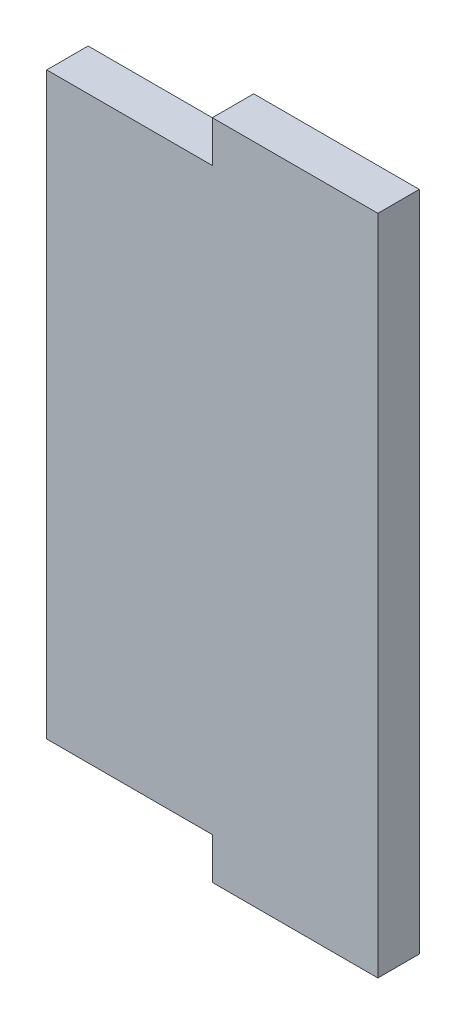
SolidWorks part; units mm, degrees
ref_plane "Front Plane" through (0, 0, 0) normal (0, 0, 1) x (1, 0, 0)
ref_plane "Top Plane" through (0, 0, 0) normal (0, 1, 0) x (1, 0, 0)
ref_plane "Right Plane" through (0, 0, 0) normal (1, 0, 0) x (0, 0, -1)
sketch "Sketch1" plane through (0, 0, 0) normal (0, 0, 1) x (1, 0, 0)
  line L1 (98.425, 0) -> (85.725, 0)
  line L2 (98.425, 0) -> (98.425, -50.8)
  line L3 (98.425, -50.8) -> (85.725, -50.8)
  line L4 (73.025, -3.175) -> (73.025, -47.625)
  line L7 (73.025, -47.625) -> (85.725, -47.625)
  line L8 (85.725, -50.8) -> (85.725, -47.625)
  line L11 (73.025, -3.175) -> (85.725, -3.175)
  line L12 (85.725, 0) -> (85.725, -3.175)
extrude "Boss-Extrude1" add sketch "Sketch1" along normal blind 3.175 contours L2 L3 L8 L7 L4 L11 L12 L1
